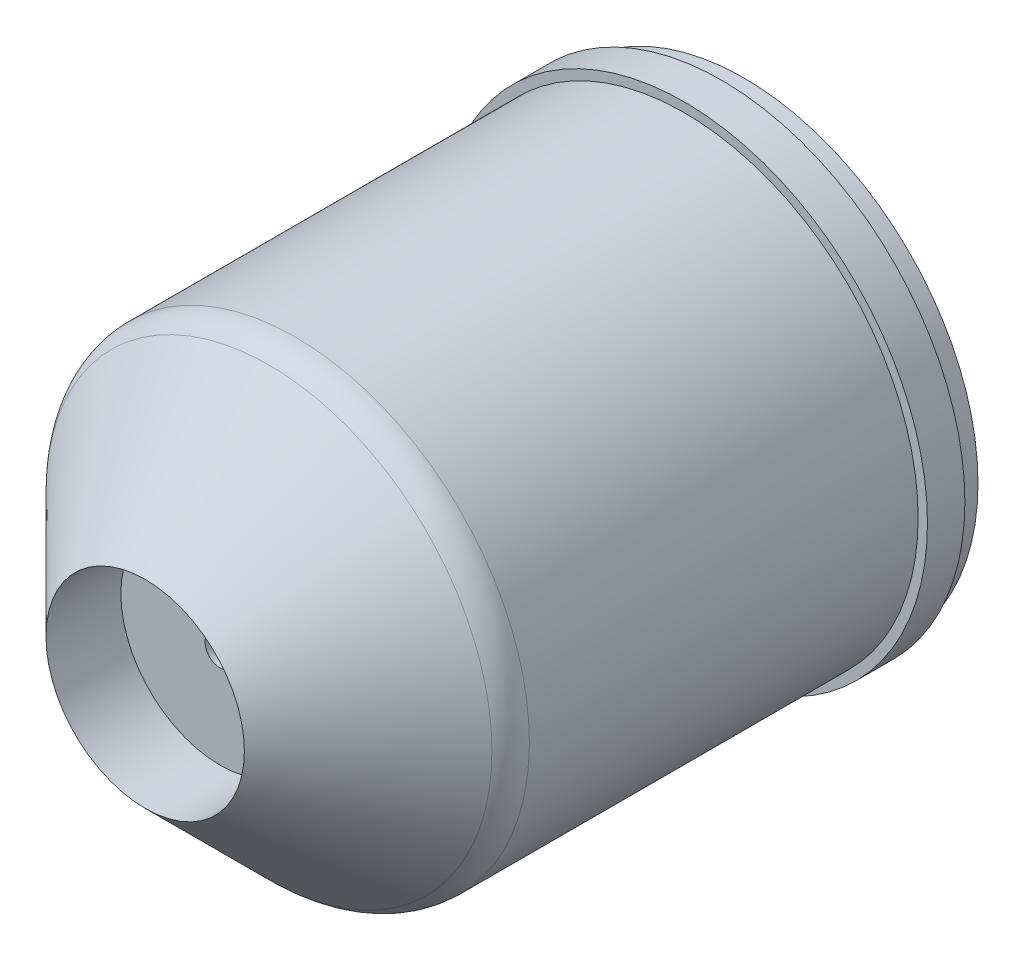
SolidWorks part; units mm, degrees
ref_plane "Front Plane" through (0, 0, 0) normal (0, 0, 1) x (1, 0, 0)
ref_plane "Top Plane" through (0, 0, 0) normal (0, 1, 0) x (1, 0, 0)
ref_plane "Right Plane" through (0, 0, 0) normal (1, 0, 0) x (0, 0, -1)
sketch "Sketch1" plane through (0, 0, 0) normal (0, 0, 1) x (1, 0, 0)
  circle A0 centre (0, 0) radius 31.25
  dimension "D1" = 62.5
extrude "Boss-Extrude1" add sketch "Sketch1" along normal blind 80
ref_plane "Plane1" through (0, 0, 3) normal (0, 0, 1) x (1, 0, 0)
sketch "Sketch2" plane through (0, 0, 3) normal (0, 0, 1) x (1, 0, 0)
  circle A0 centre (0, 0) radius 32.5
  dimension "D1" = 65
extrude "Boss-Extrude2" add sketch "Sketch2" along normal blind 5
chamfer "Chamfer1" distance 18 angle 45 1 edges at (31.25, 0, 80)
fillet "Fillet2" radius 5 1 edges at (31.25, 0, 62)
sketch "Sketch6" plane through (0, 0, 80) normal (0, 0, 1) x (1, 0, 0)
  circle A0 centre (0, 0) radius 13.25
  dimension "D1" = 26.5
extrude "Cut-Extrude3" cut sketch "Sketch6" against normal blind 10
sketch "Sketch7" plane through (0, 0, 0) normal (0, 0, -1) x (-1, 0, 0)
  circle A0 centre (0, 0) radius 28.75
  dimension "D1" = 57.5
extrude "Cut-Extrude4" cut sketch "Sketch7" against normal blind 60
sketch "Sketch8" plane through (0, 0, 70) normal (0, 0, 1) x (1, 0, 0)
  circle A0 centre (0, 0) radius 2
  circle A1 centre (8.0963, 0) radius 2.5
  dimension "D1" = 4
  dimension "D2" = 5
  dimension "D3" = 8.0963
extrude "Cut-Extrude5" cut sketch "Sketch8" against normal through all
